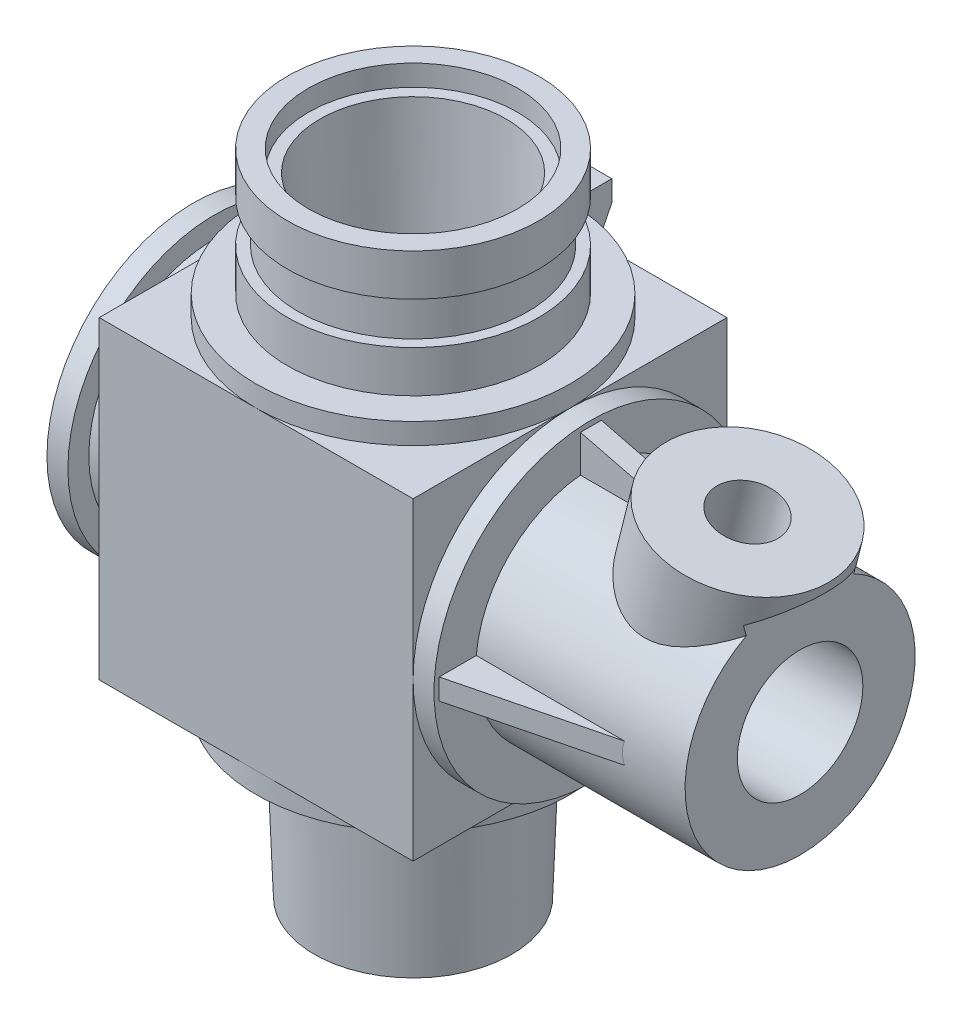
SolidWorks part; units mm, degrees
material "Gray Cast Iron"
ref_plane "Front" through (0, 0, 0) normal (0, 0, 1) x (1, 0, 0)
ref_plane "Top" through (0, 0, 0) normal (0, 1, 0) x (1, 0, 0)
ref_plane "Right" through (0, 0, 0) normal (1, 0, 0) x (0, 0, -1)
sketch "Sketch1" plane through (0, 0, 0) normal (1, 0, 0) x (0, 0, -1)
  line L1 (7.5, 7.5) -> (-7.5, 7.5)
  line L2 (7.5, 7.5) -> (7.5, -7.5)
  line L3 (7.5, -7.5) -> (-7.5, -7.5)
  line L4 (-7.5, 7.5) -> (-7.5, -7.5)
  line L5 (7.5, 7.5) -> (-7.5, -7.5) construction
  line L6 (7.5, -7.5) -> (-7.5, 7.5) construction
  point P0 (0, 0)
  dimension "D1" = 15
  dimension "D2" = 15
extrude "Boss-Extrude2" add sketch "Sketch1" along normal blind 15
sketch "Sketch3" plane through (0, 7.5, 0) normal (0, 1, 0) x (1, 0, 0)
  line L0 (0, 0) -> (15, 0) construction
  line L1 (0, 7.5) -> (0, -7.5) construction
  line L2 (15, 7.5) -> (15, -7.5) construction
  line L3 (7.5, 7.5) -> (7.5, -7.5) construction
  line L4 (15, 7.5) -> (0, 7.5) construction
  line L5 (15, -7.5) -> (0, -7.5) construction
  circle A0 centre (7.5, 0) radius 7.5
extrude "Boss-Extrude3" add sketch "Sketch3" along normal blind 1
sketch "Sketch4" plane through (0, 8.5, 0) normal (0, 1, 0) x (1, 0, 0)
  circle A0 centre (7.5, 0) radius 6
  dimension "D1" = 12
extrude "Boss-Extrude4" add sketch "Sketch4" along normal blind 2
sketch "Sketch5" plane through (0, 10.5, 0) normal (0, 1, 0) x (1, 0, 0)
  circle A0 centre (7.5, 0) radius 5.5
extrude "Boss-Extrude5" add sketch "Sketch5" along normal blind 2
sketch "Sketch6" plane through (0, 12.5, 0) normal (0, 1, 0) x (1, 0, 0)
  circle A0 centre (7.5, 0) radius 6
extrude "Boss-Extrude6" add sketch "Sketch6" along normal blind 2
sketch "Sketch7" plane through (0, -7.5, 0) normal (0, -1, 0) x (1, 0, 0)
  line L0 (7.5, 7.5) -> (7.5, -7.5) construction
  line L1 (15, 7.5) -> (0, 7.5) construction
  line L2 (15, -7.5) -> (0, -7.5) construction
  circle A0 centre (7.5, 0) radius 7.5
extrude "Boss-Extrude7" add sketch "Sketch7" along normal blind 1
sketch "Sketch8" plane through (0, -8.5, 0) normal (0, -1, 0) x (1, 0, 0)
  circle A0 centre (7.5, 0) radius 5
  dimension "D1" = 10
extrude "Boss-Extrude8" add sketch "Sketch8" along normal blind 8 draft 2
sketch "Sketch9" plane through (0, -16.5, 0) normal (0, -1, 0) x (1, 0, 0)
  circle A0 centre (7.5, 0) radius 3.5
extrude "Cut-Extrude1" cut sketch "Sketch9" against normal blind 21
sketch "Sketch10" plane through (0, 4.5, 0) normal (0, -1, 0) x (1, 0, 0)
  circle A0 centre (7.5, 0) radius 3.5
sketch "Sketch18" plane through (15, 0, 0) normal (1, 0, 0) x (0, 0, -1)
  circle A0 centre (0, 0) radius 7.5
extrude "Boss-Extrude11" add sketch "Sketch18" along normal blind 1
sketch "Sketch19" plane through (16, 0, 0) normal (1, 0, 0) x (0, 0, -1)
  circle A0 centre (0, 0) radius 5.5
extrude "Boss-Extrude12" add sketch "Sketch19" along normal blind 10
ref_plane "Plane2" through (0, 0, 0) normal (0, 0, 1) x (1, 0, 0)
sketch "Sketch23" plane through (0, 0, 0) normal (-1, 0, 0) x (0, 0, 1)
  circle A0 centre (0, 0) radius 6
extrude "Boss-Extrude14" add sketch "Sketch23" along normal blind 2
sketch "Sketch24" plane through (-2, 0, 0) normal (-1, 0, 0) x (0, 0, 1)
  circle A0 centre (0, 0) radius 7
extrude "Boss-Extrude15" add sketch "Sketch24" along normal blind 1
sketch "Sketch28" plane through (26, 0, 0) normal (1, 0, 0) x (0, 0, -1)
  circle A0 centre (0, 0) radius 6
sketch "Sketch29" plane through (-3, 0, 0) normal (-1, 0, 0) x (0, 0, 1)
  circle A0 centre (0, 0) radius 5.5
extrude "Cut-Extrude5" cut sketch "Sketch29" against normal blind 17
sketch "Sketch30" plane through (26, 0, 0) normal (1, 0, 0) x (0, 0, -1)
  circle A0 centre (0, 0) radius 3
extrude "Cut-Extrude6" cut sketch "Sketch30" against normal blind 18
ref_plane "Plane4" through (2, 0, 0) normal (-1, 0, 0) x (0, 0, 1)
sketch "Sketch40" plane through (0, 14.5, 0) normal (0, 1, 0) x (1, 0, 0)
  circle A0 centre (7.5, 0) radius 4.5
extrude "Cut-Extrude10" cut sketch "Sketch40" against normal blind 11 draft 2.9
sketch "Sketch41" plane through (0, 14.5, 0) normal (0, 1, 0) x (1, 0, 0)
  circle A0 centre (7.5, 0) radius 5
extrude "Cut-Extrude11" cut sketch "Sketch41" against normal blind 1
sketch "Sketch42" plane through (0, 7.5, 0) normal (0, 1, 0) x (1, 0, 0)
  line L0 (7.5, 7.5) -> (7.5, 9.5)
  line L1 (7.5, 9.5) -> (0, 9.5)
  line L2 (0, 9.5) -> (0, 0)
  circle A0 centre (7.5, 0) radius 7.5 construction
  arc A1 (7.5, 7.5) -> (0, 0) centre (7.5, 0) ccw
  arc M1 (0, 0) -> (7.5, 7.5) centre (7.5, 0) cw
  line M2 (7.5, 7.5) -> (0, 7.5)
  line M3 (0, 7.5) -> (0, 0)
extrude "Boss-Extrude17" add sketch "Sketch42" along normal blind 1 contours M3 M1 M2 | L1 L2 L0 M2
sketch "Sketch43" plane through (7.5, 0, 0) normal (1, 0, 0) x (0, 0, -1)
  line L0 (7.5, 7.5) -> (7.5, 3.5)
  line L1 (7.5, 0) -> (7.5, 7.5) construction
  line L2 (7.5, 3.5) -> (9.5, 7.5)
  line L3 (9.5, 7.5) -> (7.5, 7.5)
extrude "Boss-Extrude18" add sketch "Sketch43" against normal blind 7.5
sketch "Sketch44" plane through (0, 0, 0) normal (-1, 0, 0) x (0, 0, 1)
  line L0 (-9.5, 8.5) -> (-7.5, 8.5) construction
  line L1 (-9.5, 8.5) -> (0, 8.5) construction
ref_plane "Plane5" through (2, 0, 0) normal (-1, 0, 0) x (0, 0, 1)
sketch "Sketch46" plane through (2, 0, 0) normal (-1, 0, 0) x (0, 0, 1)
  line L0 (-7.5, 8.5) -> (-2.2683, -1.9633) construction
  line L1 (-7.5, 3.5) -> (-9.5, 7.5) construction
  line L2 (-7.3294, 8.1588) -> (-4.6461, 9.5005)
  line L3 (-4.6461, 9.5005) -> (-5.8218, 11.8517)
  line L4 (-5.8218, 11.8517) -> (-8.505, 10.5101)
  line L5 (-8.505, 10.5101) -> (-7.3294, 8.1588)
  circle A0 centre (0, 0) radius 3 construction
revolve "Revolve1" add sketch "Sketch46" angle 360 about L5
sketch "Sketch47" plane through (0, 11.8101, -5.905) normal (0, 0.8944, -0.4472) x (1, 0, 0)
  circle A0 centre (2, 2.9069) radius 3
extrude "Cut-Extrude12" cut sketch "Sketch47" against normal blind 4
sketch "Sketch48" plane through (0, 8.2324, -4.1162) normal (0, 0.8944, -0.4472) x (1, 0, 0)
  line L0 (0, 4.6957) -> (0, 2.9069) construction
  circle A0 centre (2, 2.9069) radius 1
  dimension "D1" = 2
extrude "Cut-Extrude13" cut sketch "Sketch48" against normal blind 7
cosmetic thread "Cosmetic Thread2" parameters "D2"=3
ref_plane "Plane7" through (0, 0, 0) normal (0, 1, 0) x (1, 0, 0)
sketch "Sketch51" plane through (0, 0, 0) normal (0, 1, 0) x (1, 0, 0)
  line L0 (15, 7.5) -> (23, 5.5)
  line L1 (26, 5.5) -> (16, 5.5) construction
  line L2 (16, -7.5) -> (16, 7.5) construction
  dimension "D1" = 7
rib "Rib2" sketch "Sketch51" sketch "Sketch51" thickness 1 extrusion direction parallel to sketch draft on no parameters "D1"=1
pattern_circular "CirPattern2" count 4 over 360 about axis through (0, 0, 0) along (1, 0, 0) skipping 3 of "Rib2"
ref_plane "Plane8" through (0, 0, 0) normal (0, 0, 1) x (1, 0, 0)
sketch "Sketch52" plane through (0, 0, 0) normal (0, 0, 1) x (1, 0, 0)
  line L0 (15, 7.5) -> (23, 5.5) construction
  line L1 (26, 5.5) -> (16, 5.5) construction
  line L2 (16, -7.5) -> (16, 7.5) construction
  dimension "D1" = 7
ref_plane "Plane9" through (2.6471, 10.5882, 0) normal (-0.2425, -0.9701, 0) x (-0.9701, 0.2425, 0)
sketch "Sketch53" plane through (2.6471, 10.5882, 0) normal (-0.2425, -0.9701, 0) x (-0.9701, 0.2425, 0)
  line L0 (-12.7331, 0) -> (-20.9793, 0) construction
  line L1 (-12.1827, 0) -> (12.1827, 0) construction
  circle A0 centre (-20.9793, 0) radius 4
extrude "Boss-Extrude19" add sketch "Sketch53" along normal blind 3 and the other way blind 2
extrude "Cut-Extrude15" cut sketch "Sketch28" along normal blind 3 contours A0
sketch "Sketch54" plane through (3.1321, 12.5285, 0) normal (0.2425, 0.9701, 0) x (0.9701, -0.2425, 0)
  circle A0 centre (20.9793, 0) radius 1.5
extrude "Cut-Extrude16" cut sketch "Sketch54" against normal blind 7
cosmetic thread "Cosmetic Thread3" parameters "D2"=4
sketch "Sketch55" plane through (0, 0, 0) normal (0, 0, 1) x (1, 0, 0)
  line L0 (15, 7.5) -> (19.1194, 6.4701)
  line L1 (15, 7.5) -> (23, 5.5) construction
  line L2 (19.6045, 8.4104) -> (18.8769, 5.5) construction
rib "Rib3" sketch "Sketch55" sketch "Sketch55" thickness 1 extrusion direction parallel to sketch draft on no parameters "D1"=1
sketch "Sketch56" plane through (26, 0, 0) normal (1, 0, 0) x (0, 0, -1)
  circle A0 centre (0, 0) radius 3
extrude "Cut-Extrude17" cut sketch "Sketch56" against normal blind 7
